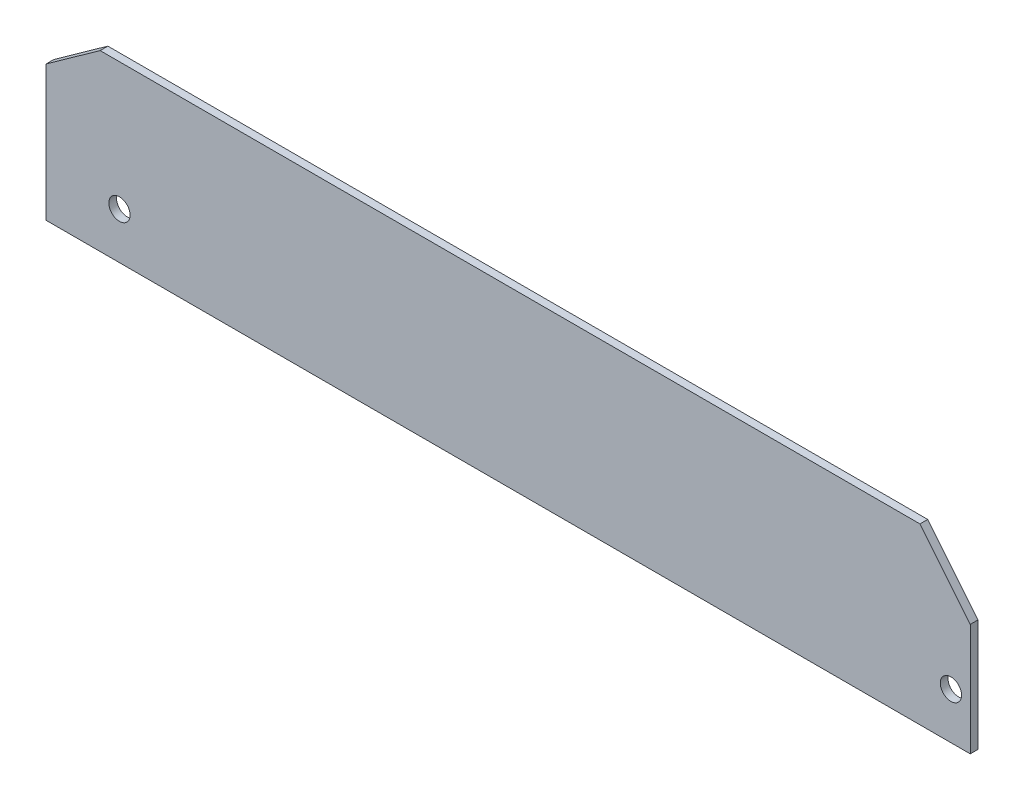
SolidWorks part; units mm, degrees
ref_plane "Front Plane" through (0, 0, 0) normal (0, 0, 1) x (1, 0, 0)
ref_plane "Top Plane" through (0, 0, 0) normal (0, 1, 0) x (1, 0, 0)
ref_plane "Right Plane" through (0, 0, 0) normal (1, 0, 0) x (0, 0, -1)
sketch "Low side shield with ends chamfered profile" plane through (0, 0, 0) normal (0, 0, 1) x (1, 0, 0)
  line L0 (-136, 7) -> (103, 7)
  line L1 (103, 7) -> (103, 36)
  line L2 (103, 36) -> (90, 52)
  line L3 (90, 52) -> (-122, 52)
  line L4 (-122, 52) -> (-136, 42)
  line L5 (-136, 42) -> (-136, 7)
  circle A0 centre (-117, 19) radius 2.75
  circle A1 centre (98, 19) radius 2.75
extrude "Low side shield with ends chamfered" add sketch "Low side shield with ends chamfered profile" along normal blind 2
